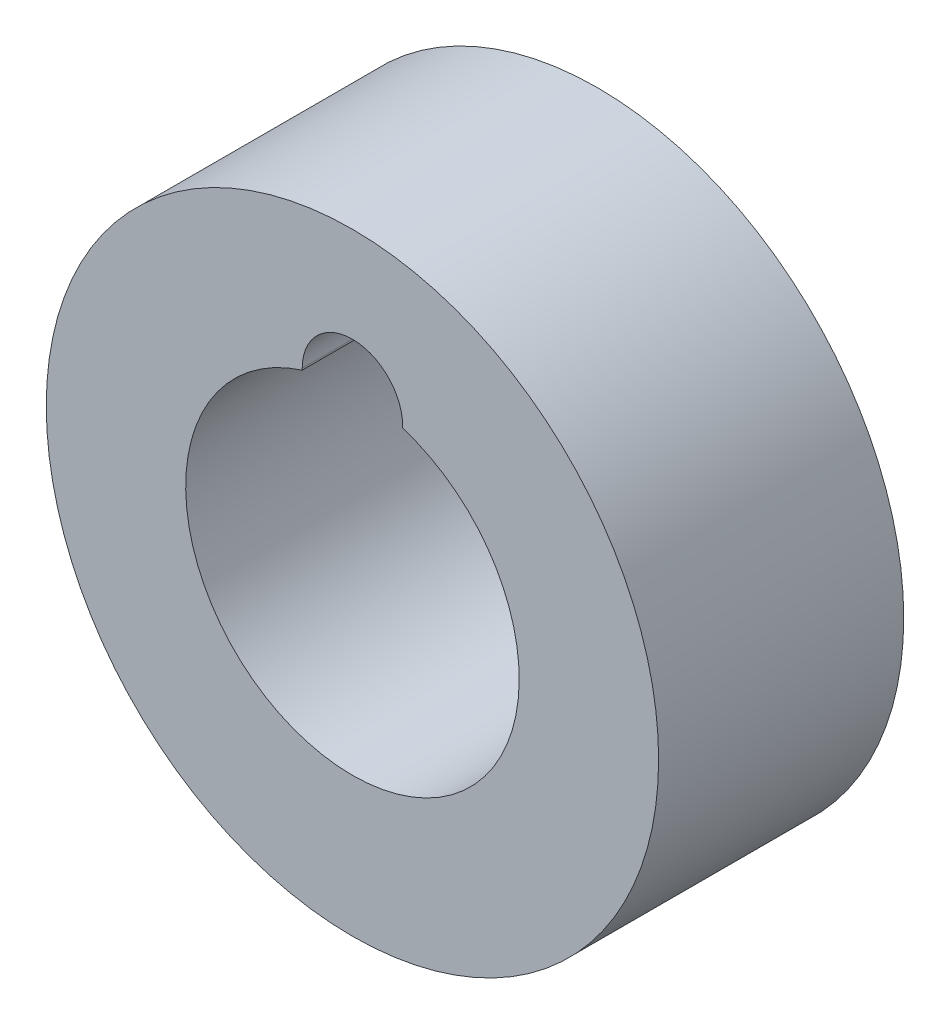
SolidWorks part; units mm, degrees
ref_plane "Alzado" through (0, 0, 0) normal (0, 0, 1) x (1, 0, 0)
ref_plane "Planta" through (0, 0, 0) normal (0, 1, 0) x (1, 0, 0)
ref_plane "Vista lateral" through (0, 0, 0) normal (1, 0, 0) x (0, 0, -1)
sketch "Croquis1" plane through (0, 0, 0) normal (0, 0, 1) x (1, 0, 0)
  circle A0 centre (0, 0) radius 4.15
  circle A1 centre (0, 0) radius 7.62
  dimension "D1" = 8.3
  dimension "D2" = 15.24
extrude "Saliente-Extruir1" add sketch "Croquis1" along normal blind 6.1
sketch "Croquis2" plane through (0, 0, 6.1) normal (0, 0, 1) x (1, 0, 0)
  line L0 (0, 0) -> (0, 4) construction
  line L1 (-1.25, 0) -> (-1.25, 4)
  line L2 (1.25, 0) -> (1.25, 4)
  circle A0 centre (0, 0) radius 4 construction
  arc A1 (-1.25, 0) -> (1.25, 0) centre (0, 0) ccw
  arc A2 (1.25, 4) -> (-1.25, 4) centre (0, 4) ccw
  point P4 (0, 2)
  dimension "D1" = 8
  dimension "D2" = 1.25
extrude "Cortar-Extruir1" cut sketch "Croquis2" against normal through all
